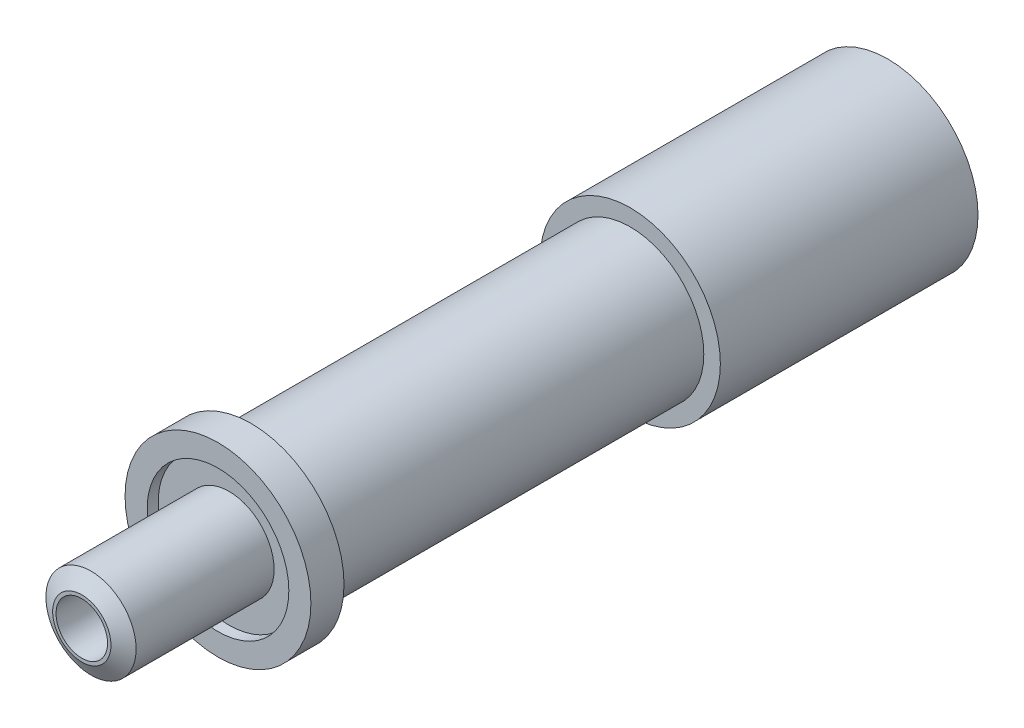
SolidWorks part; units mm, degrees
ref_plane "Front Plane" through (0, 0, 0) normal (0, 0, 1) x (1, 0, 0)
ref_plane "Top Plane" through (0, 0, 0) normal (0, 1, 0) x (1, 0, 0)
ref_plane "Right Plane" through (0, 0, 0) normal (1, 0, 0) x (0, 0, -1)
sketch "Sketch1" plane through (0, 0, 0) normal (0, 1, 0) x (1, 0, 0)
  line L0 (0, 24.784) -> (0, 10.1)
  line L1 (0, 10.1) -> (0.6, 10.1)
  line L2 (0.6, 10.1) -> (0.7, 3.1)
  line L3 (0.7, 3.1) -> (0.792, 3.1)
  line L4 (0.792, 3.1) -> (1.225, 3.35)
  line L5 (1.225, 3.35) -> (1.225, 7.1)
  line L6 (1.225, 7.1) -> (1.925, 7.1)
  line L7 (1.925, 7.1) -> (1.925, 6.8)
  line L8 (1.925, 6.8) -> (2.525, 6.8)
  line L9 (2.525, 6.8) -> (2.525, 7.7)
  line L10 (2.525, 7.7) -> (2, 7.7)
  line L11 (2, 7.7) -> (2, 18)
  line L12 (2, 18) -> (2.45, 18)
  line L13 (2.45, 18) -> (2.45, 24)
  line L14 (2.45, 24) -> (4.2, 24)
  line L15 (4.2, 24) -> (4.2, 18)
  line L16 (4.2, 18) -> (5, 18)
  line L17 (5, 18) -> (5, 25)
  line L18 (0, 25.5) -> (0, 3.1) construction
  arc A0 (4.3448, 25.4753) -> (0, 24.784) centre (0, 38.784) cw
  arc A1 (5, 25) -> (4.3448, 25.4753) centre (4.5, 25) ccw
revolve "Revolve1" add sketch "Sketch1" angle 360 about L18
sketch "Sketch2" plane through (0, 0, -18) normal (0, 0, 1) x (1, 0, 0)
  circle A0 centre (0, 0) radius 2.45
  circle A1 centre (0, 0) radius 5
  dimension "D1" = 4.9
extrude "Cut-Extrude1" cut sketch "Sketch2" against normal blind 10
